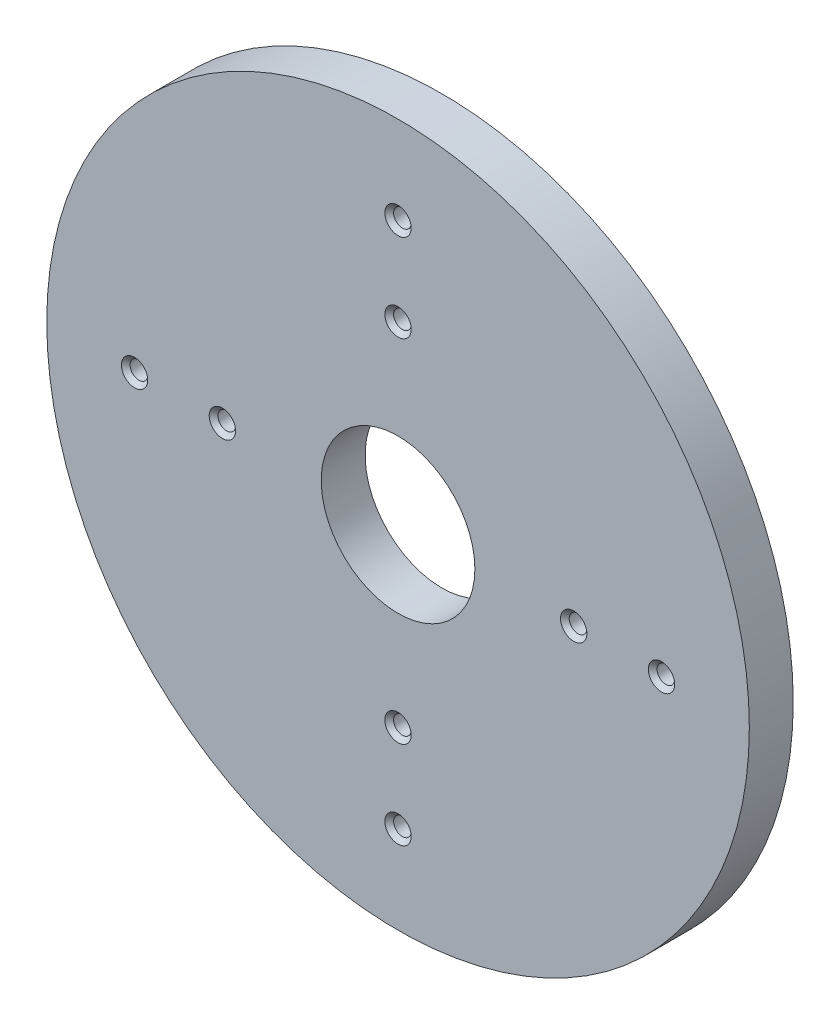
SolidWorks part; units mm, degrees
material "6061-T6 (SS)"
ref_plane "Front Plane" through (0, 0, 0) normal (0, 0, 1) x (1, 0, 0)
ref_plane "Top Plane" through (0, 0, 0) normal (0, 1, 0) x (1, 0, 0)
ref_plane "Right Plane" through (0, 0, 0) normal (1, 0, 0) x (0, 0, -1)
sketch "Sketch1" plane through (0, 0, 0) normal (0, 0, 1) x (1, 0, 0)
  circle A0 centre (0, 0) radius 101.6
  circle A1 centre (0, 0) radius 22.225
  dimension "D1" = 203.2
  dimension "D2" = 44.45
extrude "Boss-Extrude1" add sketch "Sketch1" along normal blind 12.7
hole_wizard "1/4-20 Tapped Hole1" positions "Sketch2" profile "Sketch3" tap size "1/4-20" standard "ANSI Inch" end condition up to next
sketch "Sketch2" plane through (0, 0, 12.7) normal (0, 0, 1) x (1, 0, 0)
  line L0 (0, 0) -> (0, 76.2) construction
  point P2 (0, 76.2)
  point P8 (0, 50.8)
  point P13 (76.2, 0)
  point P14 (50.8, 0)
  point P15 (0, -76.2)
  point P16 (0, -50.8)
  point P17 (-76.2, 0)
  point P18 (-50.8, 0)
  dimension "D1" = 50.8
  dimension "D2" = 76.2
  dimension "D3" = 4
cosmetic thread "Hole Thread1"
cosmetic thread "Hole Thread2"
cosmetic thread "Hole Thread3"
cosmetic thread "Hole Thread4"
cosmetic thread "Hole Thread5"
cosmetic thread "Hole Thread6"
cosmetic thread "Hole Thread7"
cosmetic thread "Hole Thread8"
sketch "Sketch3" plane through (-50.8, 0, 12.7) normal (1, 0, 0) x (0, -1, 0)
  line L0 (0, 0) -> (0, 12.7)
  line L1 (0, 12.7) -> (3.81, 12.7)
  line L2 (2.5527, 11.4427) -> (2.5527, 1.2573)
  line L3 (2.5527, 1.2573) -> (3.81, 0)
  line L5 (3.81, 0) -> (0, 0)
  line L6 (-2.5527, 1.2573) -> (-3.81, 0) construction
  line L7 (3.81, 12.7) -> (2.5527, 11.4427)
  line L8 (-3.81, 12.7) -> (-2.5527, 11.4427) construction
  line L11 (0, -6.35) -> (0, 107.95) construction
  dimension "Thru Tap Drill Dia." = 5.1054
  dimension "Thru Tap Drill Depth" = 12.7
  dimension "Near C'Sink Dia." = 7.62
  dimension "Near C'Sink Angle" = 90
  dimension "Far C'Sink Dia." = 7.62
  dimension "Far C'Sink Angle" = 90
